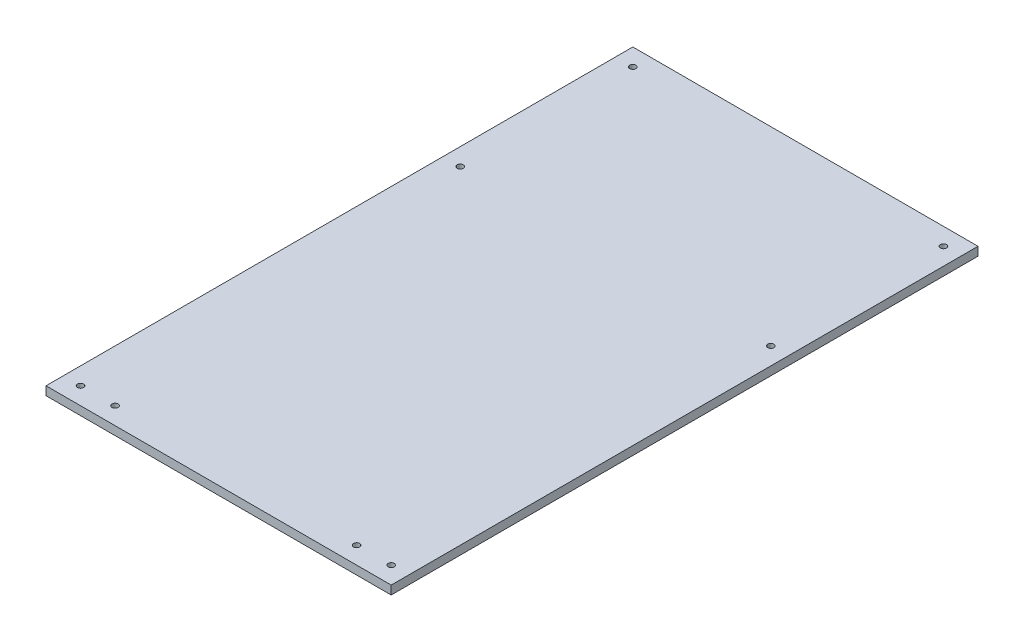
SolidWorks part; units mm, degrees
ref_plane "Front" through (0, 0, 0) normal (0, 0, 1) x (1, 0, 0)
ref_plane "Top" through (0, 0, 0) normal (0, 1, 0) x (1, 0, 0)
ref_plane "Right" through (0, 0, 0) normal (1, 0, 0) x (0, 0, -1)
sketch "Sketch1" plane through (0, 0, 0) normal (0, 1, 0) x (1, 0, 0)
  line L1 (0, 0) -> (127, 0)
  line L2 (0, 0) -> (0, 215.9)
  line L3 (0, 215.9) -> (127, 215.9)
  line L4 (127, 0) -> (127, 215.9)
  dimension "D1" = 215.9
  dimension "D2" = 127
extrude "Boss-Extrude1" add sketch "Sketch1" along normal blind 3.175
hole_wizard "#43 (0.089) Diameter Hole1" positions "Sketch4" profile "Sketch3" hole size "#43" standard "ANSI Inch" end condition through all
sketch "Sketch4" plane through (0, 3.175, 0) normal (0, 1, 0) x (1, 0, 0)
  line L0 (127, 215.9) -> (0, 215.9) construction
  line L1 (0, 215.9) -> (0, 0) construction
  point P0 (6.35, 209.55)
  point P1 (6.35, 209.55)
  point P16 (120.65, 209.55)
  point P17 (120.65, 146.05)
  point P18 (6.35, 146.05)
  point P25 (120.65, 209.55)
  point P26 (120.65, 6.35)
  point P27 (6.35, 6.35)
  point P30 (19.05, 6.35)
  point P34 (107.95, 6.35)
  dimension "D1" = 6.35
  dimension "D2" = 6.35
  dimension "D3" = 2
  dimension "D4" = 2
  dimension "D5" = 2
  dimension "D6" = 2
  dimension "D7" = 2
  dimension "D8" = 2
sketch "Sketch3" plane through (6.35, 3.175, -209.55) normal (1, 0, 0) x (0, 0, 1)
  line L0 (0, 0) -> (0, 3.175)
  line L1 (0, 3.175) -> (1.1303, 3.175)
  line L2 (1.1303, 3.175) -> (1.1303, 0)
  line L5 (1.1303, 0) -> (0, 0)
  line L11 (0, -6.35) -> (0, 107.95) construction
  dimension "Thru Hole Dia." = 2.2606
  dimension "Thru Hole Depth" = 3.175
